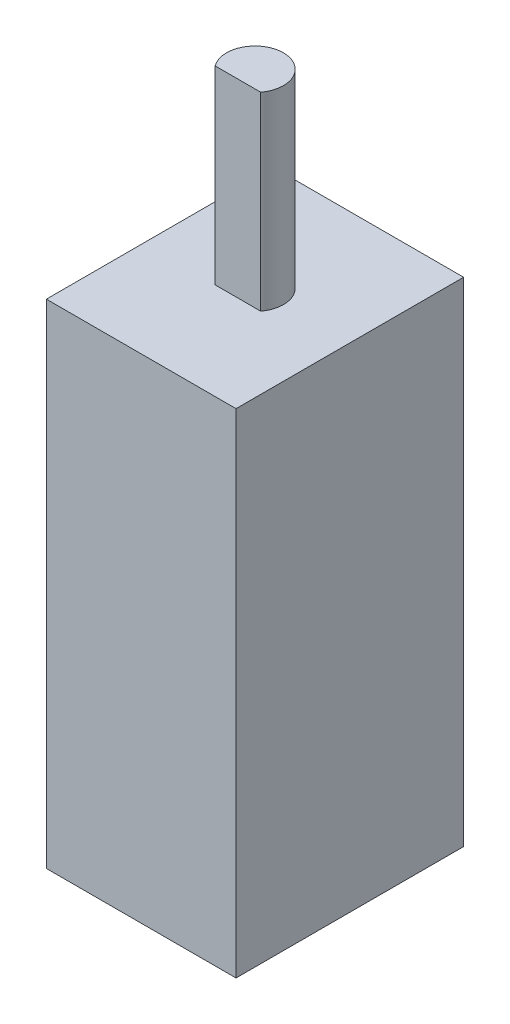
SolidWorks part; units mm, degrees
ref_plane "Front Plane" through (0, 0, 0) normal (0, 0, 1) x (1, 0, 0)
ref_plane "Top Plane" through (0, 0, 0) normal (0, 1, 0) x (1, 0, 0)
ref_plane "Right Plane" through (0, 0, 0) normal (1, 0, 0) x (0, 0, -1)
sketch "Sketch2" plane through (0, 0, 0) normal (0, 1, 0) x (1, 0, 0)
  line L1 (-5, 6) -> (5, 6)
  line L2 (-5, 6) -> (-5, -6)
  line L3 (-5, -6) -> (5, -6)
  line L4 (5, 6) -> (5, -6)
  line L5 (-5, 6) -> (5, -6) construction
  line L6 (-5, -6) -> (5, 6) construction
  point P0 (0, 0)
  dimension "D1" = 10
  dimension "D2" = 12
extrude "Boss-Extrude1" add sketch "Sketch2" along normal blind 26
sketch "Sketch3" plane through (0, 26, 0) normal (0, 1, 0) x (1, 0, 0)
  line L0 (0, 1.5) -> (0, -0.9) construction
  line L1 (-1.2, -0.9) -> (1.2, -0.9)
  circle A0 centre (0, 0) radius 1.5
  point P8 (0, -0.9)
  dimension "D1" = 3
  dimension "D2" = 2.4
extrude "Boss-Extrude2" add sketch "Sketch3" along normal blind 10 contours L0 A0 L1 | A0 L0 L1
